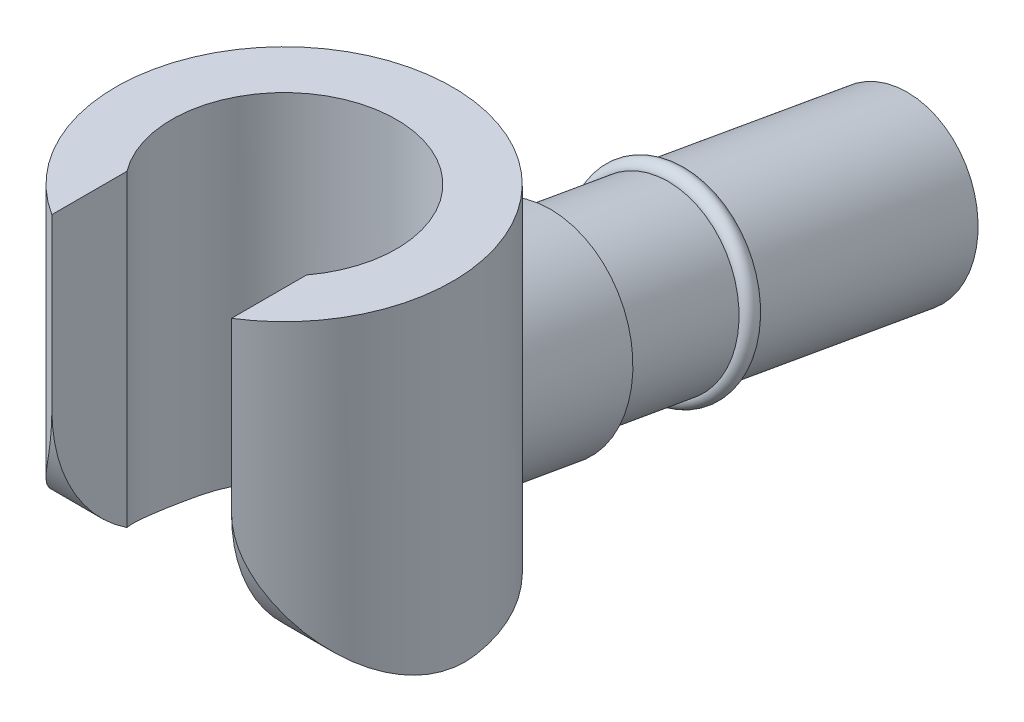
SolidWorks part; units mm, degrees
material "ABS"
ref_plane "Front Plane" through (0, 0, 0) normal (0, 0, 1) x (1, 0, 0)
ref_plane "Top Plane" through (0, 0, 0) normal (0, 1, 0) x (1, 0, 0)
ref_plane "Right Plane" through (0, 0, 0) normal (1, 0, 0) x (0, 0, -1)
sketch "Sketch2" plane through (0, 0, 0) normal (0, 1, 0) x (1, 0, 0)
  circle A0 centre (0, 0) radius 2.3813
  circle A1 centre (0, 0) radius 1.5875
  dimension "D1" = 4.7625
  dimension "D2" = 3.175
extrude "Boss-Extrude1" add sketch "Sketch2" along normal blind 4.7625
sketch "Sketch3" plane through (0, 4.7625, 0) normal (0, 1, 0) x (1, 0, 0)
  line L1 (-1.27, -3.4925) -> (1.27, -3.4925)
  line L2 (-1.27, -3.4925) -> (-1.27, -0.9525)
  line L3 (-1.27, -0.9525) -> (1.27, -0.9525)
  line L4 (1.27, -3.4925) -> (1.27, -0.9525)
  circle A0 centre (0, 0) radius 1.5875 construction
  dimension "D1" = 2.54
  dimension "D2" = 2.54
extrude "Cut-Extrude1" cut sketch "Sketch3" against normal through all
sketch "Sketch4" plane through (-1.27, 0, 0) normal (1, 0, 0) x (0, 0, -1)
  line L0 (-2.0143, 4.7625) -> (-2.0143, 2.3813) construction
  line L1 (2.3813, 0) -> (0.3669, 0) construction
  line L2 (-2.0143, 0) -> (2.3813, 0) construction
  line L3 (-2.0143, 4.7625) -> (-2.0143, 0) construction
  line L4 (0.3669, 0) -> (-2.0143, 0)
  line L5 (-2.0143, 0) -> (-2.0143, 2.3813)
  arc A0 (-2.0143, 2.3813) -> (0.3669, 0) centre (0.3669, 2.3813) ccw
  dimension "D1" = 2.3813
  dimension "D2" = 2.3813
  dimension "D3" = 2.3813
extrude "Cut-Extrude2" cut sketch "Sketch4" against normal through all and the other way through all
sketch "Sketch5" plane through (0, 0, 0) normal (1, 0, 0) x (0, 0, -1)
  line L0 (2.3813, 1.5875) -> (8.6348, 0.4848) construction
  line L1 (2.3813, 0) -> (2.3813, 4.7625) construction
  line L2 (2.3813, 4.7625) -> (-2.0143, 4.7625) construction
  dimension "D1" = 100
  dimension "D2" = 3.175
  dimension "D3" = 6.35
ref_plane "Plane1" through (0, 0.4848, -8.6348) normal (0, -0.1736, -0.9848) x (-1, 0, 0)
sketch "Sketch6" plane through (0, 0.4848, -8.6348) normal (0, -0.1736, -0.9848) x (-1, 0, 0)
  line L0 (-2.3813, 2.7133) -> (2.3813, 2.7133) construction
  line L1 (0, 3.1268) -> (0, -0.1752) construction
  line L4 (0, 3.1268) -> (0, 3.5411) construction
  circle A0 centre (0, -0.1752) radius 1.1906
  ellipse E1 centre (0, 2.7133) end of major axis (2.3812, 2.7133) minor radius 0.4135 (1.27, 2.3635) -> (-1.27, 2.3635) ccw construction
  dimension "D1" = 2.3813
  dimension "D2" = 3.302
extrude "Boss-Extrude2" add sketch "Sketch6" against normal up to surface (6.529 mm away)
sketch "Sketch7" plane through (0, -1.462, -8.2915) normal (0, -0.1736, -0.9848) x (-1, 0, 0)
  circle A0 centre (0, 1.8016) radius 1.3881
  ellipse E0 centre (0, 0) end of major axis (2.3812, 0) minor radius 0.4135 (2.3528, 0.0637) -> (-2.3528, 0.0637) ccw construction
extrude "Boss-Extrude3" add sketch "Sketch7" along direction (0, -0.1736, -0.9848) on the side against the normal up to surface (1.4045 mm away) from offset 5.1594 offset against normal yes
sketch "Sketch8" plane through (0, 0, 0) normal (1, 0, 0) x (0, 0, -1)
  line L0 (8.8111, 1.4848) -> (3.7301, 2.3807) construction
  line L2 (3.2823, -0.1589) -> (3.7644, 2.5752) construction
  circle A0 centre (5.5563, 2.0587) radius 0.127
  dimension "D1" = 0.254
  dimension "D2" = 3.175
revolve "Revolve1" add sketch "Sketch8" angle 360 about axis through (0, 2.2626, 2.4563) along (0, -0.1736, -0.9848)
